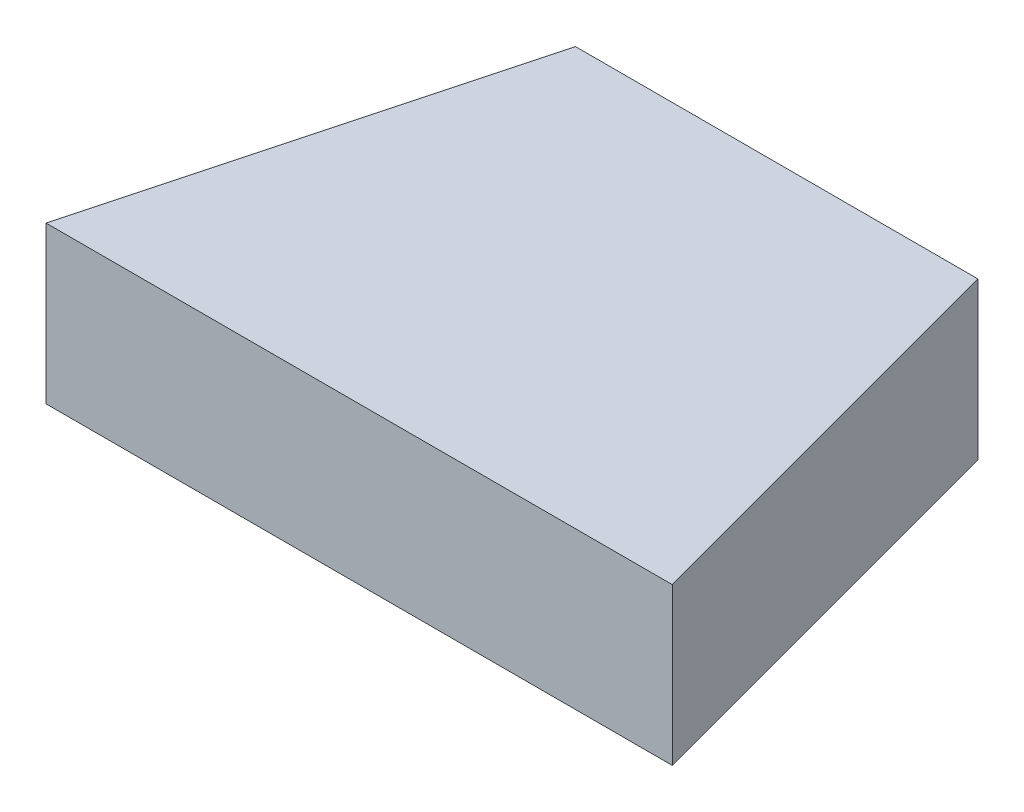
SolidWorks part; units mm, degrees
ref_plane "Front" through (0, 0, 0) normal (0, 0, 1) x (1, 0, 0)
ref_plane "Top" through (0, 0, 0) normal (0, 1, 0) x (1, 0, 0)
ref_plane "Right" through (0, 0, 0) normal (1, 0, 0) x (0, 0, -1)
sketch "Sketch1" plane through (0, 0, 0) normal (0, 1, 0) x (1, 0, 0)
  line L0 (0, 0) -> (-24.4882, -91.3911) construction
  line L1 (142.1911, -38.1) -> (142.1911, 38.1) construction
  line L2 (142.1911, 38.1) -> (104.0911, 104.0911) construction
  line L3 (104.0911, 104.0911) -> (38.1, 142.1911) construction
  line L4 (38.1, 142.1911) -> (-38.1, 142.1911) construction
  line L5 (-38.1, 142.1911) -> (-104.0911, 104.0911) construction
  line L6 (-104.0911, 104.0911) -> (-142.1911, 38.1) construction
  line L7 (-142.1911, 38.1) -> (-142.1911, -38.1) construction
  line L8 (-142.1911, -38.1) -> (-104.0911, -104.0911) construction
  line L9 (-104.0911, -104.0911) -> (-38.1, -142.1911) construction
  line L10 (-38.1, -142.1911) -> (38.1, -142.1911)
  line L11 (38.1, -142.1911) -> (104.0911, -104.0911) construction
  line L12 (104.0911, -104.0911) -> (142.1911, -38.1) construction
  line L13 (0, 0) -> (24.4882, -91.3911) construction
  line L14 (0, 0) -> (142.1911, 0) construction
  line L15 (-24.4882, -91.3911) -> (24.4882, -91.3911)
  line L16 (24.4882, -91.3911) -> (66.903, -66.903) construction
  line L17 (66.903, -66.903) -> (91.3911, -24.4882) construction
  line L18 (91.3911, -24.4882) -> (91.3911, 24.4882) construction
  line L19 (91.3911, 24.4882) -> (66.903, 66.903) construction
  line L20 (66.903, 66.903) -> (24.4882, 91.3911) construction
  line L21 (24.4882, 91.3911) -> (-24.4882, 91.3911) construction
  line L22 (-24.4882, 91.3911) -> (-66.903, 66.903) construction
  line L23 (-66.903, 66.903) -> (-91.3911, 24.4882) construction
  line L24 (-91.3911, 24.4882) -> (-91.3911, -24.4882) construction
  line L25 (-91.3911, -24.4882) -> (-66.903, -66.903) construction
  line L26 (-66.903, -66.903) -> (-24.4882, -91.3911) construction
  line L27 (-24.4882, -91.3911) -> (-38.1, -142.1911)
  line L29 (24.4882, -91.3911) -> (38.1, -142.1911)
  circle A0 centre (0, 0) radius 142.1911 construction
  dimension "D1" = 76.2
  dimension "D2" = 50.8
extrude "Boss-Extrude1" add sketch "Sketch1" along normal blind 19.05
